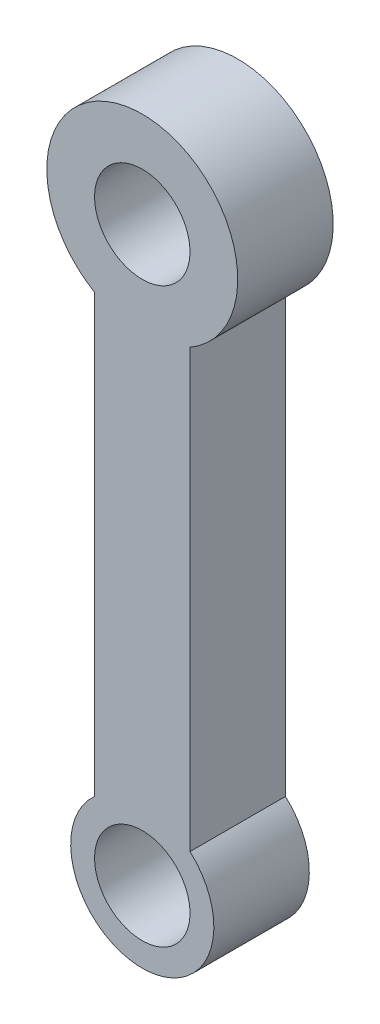
SolidWorks part; units mm, degrees
ref_plane "Front Plane" through (0, 0, 0) normal (0, 0, 1) x (1, 0, 0)
ref_plane "Top Plane" through (0, 0, 0) normal (0, 1, 0) x (1, 0, 0)
ref_plane "Right Plane" through (0, 0, 0) normal (1, 0, 0) x (0, 0, -1)
sketch "Sketch1" plane through (0, 0, 0) normal (0, 0, 1) x (1, 0, 0)
  line L3 (10, -63.1218) -> (10, 28.3773)
  line L5 (-10, 28.3773) -> (-10, -63.1218)
  arc A0 (10, 28.3773) -> (-10, 28.3773) centre (0, 45.6978) ccw
  arc A1 (-10, -63.1218) -> (10, -63.1218) centre (0, -74.3022) ccw
extrude "Boss-Extrude1" add sketch "Sketch1" along normal blind 20
sketch "Sketch2" plane through (0, 0, 0) normal (0, 0, -1) x (-1, 0, 0)
  circle A0 centre (0, 45.6978) radius 10
  circle A1 centre (0, -74.3022) radius 10
extrude "Cut-Extrude3" cut sketch "Sketch2" against normal blind 20
